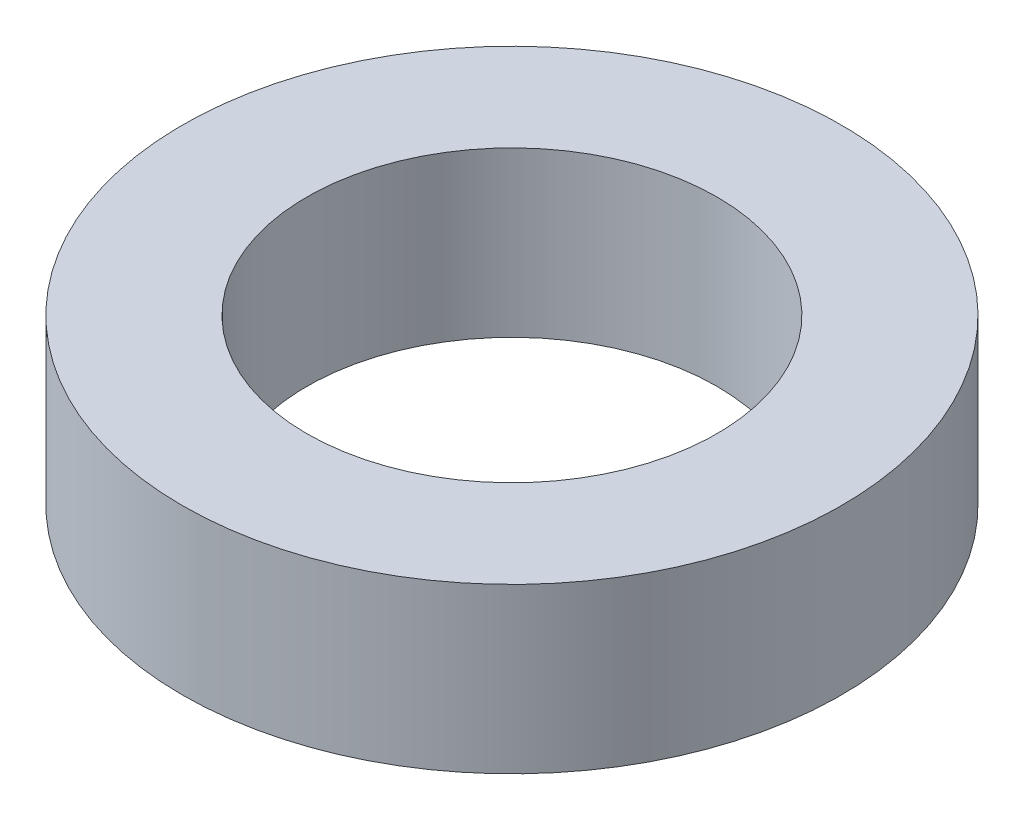
SolidWorks part; units mm, degrees
material "非常高密度 PE (SS)"
ref_plane "前视基准面" through (0, 0, 0) normal (0, 0, 1) x (1, 0, 0)
ref_plane "上视基准面" through (0, 0, 0) normal (0, 1, 0) x (1, 0, 0)
ref_plane "右视基准面" through (0, 0, 0) normal (1, 0, 0) x (0, 0, -1)
sketch "草图1" plane through (0, 0, 0) normal (0, 1, 0) x (1, 0, 0)
  circle A0 centre (0, 0) radius 14
  circle A1 centre (0, 0) radius 22.5
  dimension "D1" = 45
  dimension "D2" = 28
extrude "凸台-拉伸1" add sketch "草图1" along normal blind 11.2
